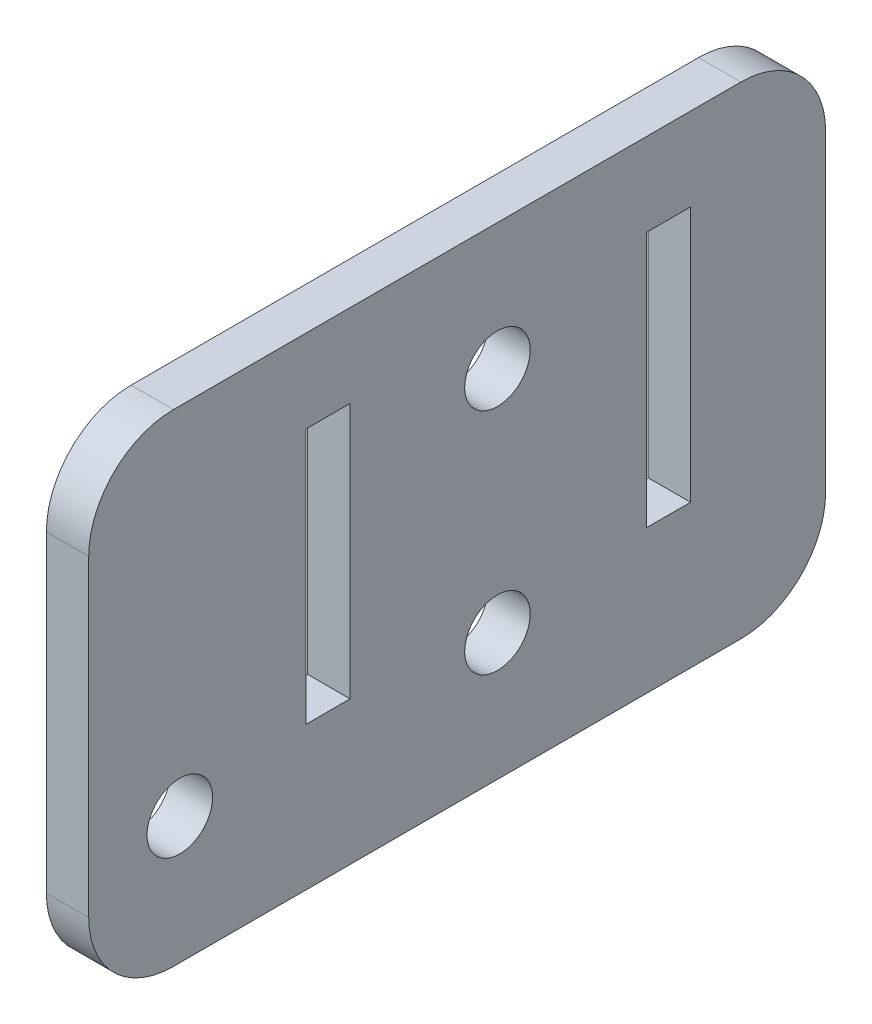
SolidWorks part; units mm, degrees
material "AISI 4340 Steel, annealed"
ref_plane "X-Y Datum" through (0, 0, 0) normal (0, 0, 1) x (1, 0, 0)
ref_plane "X-Z Datum" through (0, 0, 0) normal (0, 1, 0) x (1, 0, 0)
ref_plane "Y-Z Datum" through (0, 0, 0) normal (1, 0, 0) x (0, 0, -1)
sketch "Sketch1" plane through (0, 0, 0) normal (1, 0, 0) x (0, 0, -1)
  line L13 (55.245, 0) -> (55.245, 36.1544)
  line L14 (55.245, 36.1544) -> (0, 36.1544)
  line L16 (0, 36.1544) -> (0, 0)
  line L17 (0, 0) -> (55.245, 0)
  point P4 (-0.9293, 36.1544)
  point P6 (0, 18.0772)
  point P7 (3.0206, 36.1544)
  point P8 (0, 36.1544)
  point P9 (0, 26.034)
  point P10 (0, 35.4565)
  dimension "D1" = 55.245
  dimension "D2" = 36.1544
extrude "Boss-Extrude1" add sketch "Sketch1" along normal blind 3.175
sketch "Sketch7" plane through (0, 0, 0) normal (-1, 0, 0) x (0, 0, 1)
  line L8 (-55.245, 0) -> (-55.245, 36.1544) construction
  line L9 (-45.1202, 10.7544) -> (-41.8182, 10.7544)
  line L10 (-45.1202, 10.7544) -> (-45.1202, 29.9314)
  line L11 (-45.1202, 29.9314) -> (-41.8182, 29.9314)
  line L20 (-41.8182, 10.7544) -> (-41.8182, 29.9314)
  line L21 (-19.5932, 10.7544) -> (-16.2912, 10.7544)
  line L22 (-19.5932, 10.7544) -> (-19.5932, 29.9314)
  line L23 (-19.5932, 29.9314) -> (-16.2912, 29.9314)
  line L24 (-16.2912, 10.7544) -> (-16.2912, 29.9314)
  line L26 (-55.245, 36.1544) -> (0, 36.1544) construction
  dimension "D1" = 19.177
  dimension "D2" = 3.302
  dimension "D3" = 10.1248
  dimension "D4" = 6.223
  dimension "D5" = 22.225
extrude "Cut-Extrude1" cut sketch "Sketch7" against normal blind 3.175
sketch "Sketch8" plane through (0, 0, 0) normal (-1, 0, 0) x (0, 0, 1)
  line L0 (0, 0) -> (-55.245, 0) construction
  line L1 (-41.8182, 10.7544) -> (-41.8182, 29.9314) construction
  point P0 (-30.6422, 9.525)
  point P1 (-30.6422, 26.67)
  point P2 (-6.8297, 9.525)
  dimension "D1" = 17.145
  dimension "D2" = 9.525
  dimension "D3" = 23.8125
  dimension "D4" = 11.176
fillet "Fillet1" radius 6.35 4 edges at (1.5875, 0, 0) (1.5875, 36.1544, -55.245) (1.5875, 0, -55.245) (1.5875, 36.1544, 0)
hole_wizard "#10 (0.1935) Diameter Hole2" positions "Sketch9" profile "Sketch10" hole size "#10" standard "ANSI Inch"
sketch "Sketch9" plane through (0, 0, 0) normal (-1, 0, 0) x (0, 0, 1)
  point P0 (-30.6422, 9.525)
  point P3 (-30.6422, 26.67)
  point P6 (-6.8297, 9.525)
sketch "Sketch10" plane through (0, 9.525, -30.6422) normal (0, 1, 0) x (0, 0, 1)
  line L0 (0, 0) -> (0, 11.176)
  line L1 (0, 11.176) -> (2.4574, 9.6994)
  line L2 (2.4574, 9.6994) -> (2.4574, 0)
  line L5 (2.4574, 0) -> (0, 0)
  line L10 (0, 11.176) -> (-2.4575, 9.6994) construction
  line L11 (0, -6.35) -> (0, 107.95) construction
  dimension "Hole Dia." = 4.9149
  dimension "Hole Depth" = 11.176
  dimension "Drill Angle" = 118
